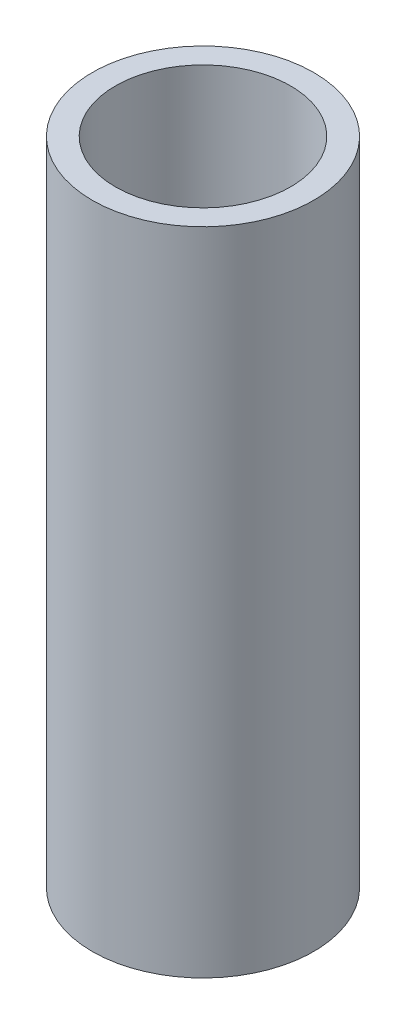
SolidWorks part; units mm, degrees
ref_plane "Front Plane" through (0, 0, 0) normal (0, 0, 1) x (1, 0, 0)
ref_plane "Top Plane" through (0, 0, 0) normal (0, 1, 0) x (1, 0, 0)
ref_plane "Right Plane" through (0, 0, 0) normal (1, 0, 0) x (0, 0, -1)
sketch "Sketch1" plane through (0, 0, 0) normal (0, 1, 0) x (1, 0, 0)
  circle A0 centre (0, 0) radius 1.702
  circle A1 centre (0, 0) radius 1.346
extrude "Boss-Extrude1" add sketch "Sketch1" along normal blind 10
